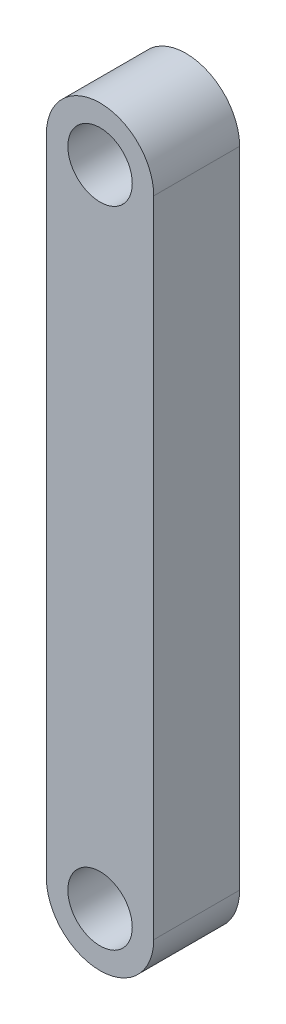
SolidWorks part; units mm, degrees
ref_plane "Ebene vorne" through (0, 0, 0) normal (0, 0, 1) x (1, 0, 0)
ref_plane "Ebene oben" through (0, 0, 0) normal (0, 1, 0) x (1, 0, 0)
ref_plane "Ebene rechts" through (0, 0, 0) normal (1, 0, 0) x (0, 0, -1)
sketch "Skizze1" plane through (0, 0, 0) normal (0, 0, 1) x (1, 0, 0)
  line L0 (0, 0) -> (0, 30) construction
  line L1 (0, 15) -> (2.4175, 15) construction
  line L2 (-2.5, 30) -> (-2.5, 0)
  line L3 (2.5, 30) -> (2.5, 0)
  circle A0 centre (0, 0) radius 1.5
  circle A1 centre (0, 0) radius 2.5
  circle A2 centre (0, 30) radius 2.5
  circle A3 centre (0, 30) radius 1.5
  dimension "D1" = 3
  dimension "D2" = 5
  dimension "D3" = 30
extrude "Aufsatz-Linear austragen1" add sketch "Skizze1" along normal blind 4 contours A2 A3 | L3 A2 L2 A1 | A1 A0
